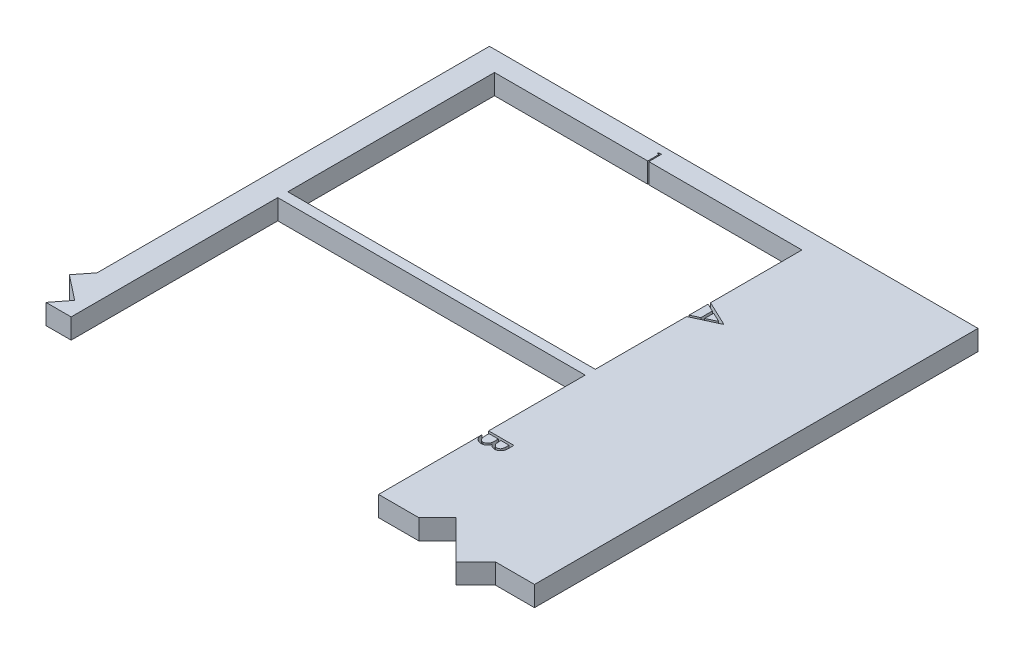
SolidWorks part; units mm, degrees
ref_plane "Front Plane" through (0, 0, 0) normal (0, 0, 1) x (1, 0, 0)
ref_plane "Top Plane" through (0, 0, 0) normal (0, 1, 0) x (1, 0, 0)
ref_plane "Right Plane" through (0, 0, 0) normal (1, 0, 0) x (0, 0, -1)
sketch "Sketch1" plane through (0, 0, 0) normal (0, 1, 0) x (1, 0, 0)
  line L0 (-146.05, 105.41) -> (-146.05, -110.49) construction
  line L1 (-146.05, -110.49) -> (-151.2076, -110.49)
  line L2 (-151.2076, -110.49) -> (-151.2076, 110.49)
  line L3 (-151.2076, 110.49) -> (151.0524, 110.49)
  line L4 (151.0524, -110.49) -> (151.0524, 110.49)
  line L5 (-55.88, 105.9659) -> (21.59, 105.9659) construction
  line L6 (-68.58, -110.49) -> (-55.88, -110.49)
  line L7 (21.59, -110.49) -> (34.29, -110.49)
  line L8 (-146.05, 105.9659) -> (-68.58, 105.9659) construction
  line L9 (-146.05, 105.41) -> (-68.58, 105.41)
  line L10 (-146.05, 105.41) -> (-146.05, 53.34)
  line L11 (-146.05, 53.34) -> (-68.58, 53.34)
  line L12 (-68.58, 105.41) -> (-68.58, 53.34)
  line L13 (-146.05, 50.8) -> (-68.58, 50.8)
  line L14 (-146.05, 50.8) -> (-146.05, -1.27)
  line L15 (-146.05, -1.27) -> (-68.58, -1.27)
  line L16 (-68.58, 50.8) -> (-68.58, -1.27)
  line L17 (-146.05, -3.81) -> (-68.58, -3.81)
  line L18 (-146.05, -3.81) -> (-146.05, -55.88)
  line L19 (-146.05, -55.88) -> (-68.58, -55.88)
  line L20 (-68.58, -3.81) -> (-68.58, -55.88)
  line L21 (-146.05, -58.42) -> (-68.58, -58.42)
  line L22 (-146.05, -58.42) -> (-146.05, -110.49)
  line L23 (34.29, 105.9659) -> (111.76, 105.9659) construction
  line L24 (-68.58, -58.42) -> (-68.58, -110.49)
  line L25 (-55.88, 105.41) -> (21.59, 105.41)
  line L26 (-55.88, 105.41) -> (-55.88, 53.34)
  line L27 (-55.88, 53.34) -> (21.59, 53.34)
  line L28 (21.59, 105.41) -> (21.59, 53.34)
  line L29 (34.29, 105.41) -> (111.76, 105.41)
  line L30 (34.29, 105.41) -> (34.29, 53.34)
  line L31 (34.29, 53.34) -> (111.76, 53.34)
  line L32 (111.76, 105.41) -> (111.76, 53.34)
  line L33 (-55.88, -1.27) -> (21.59, -1.27)
  line L34 (-55.88, -1.27) -> (-55.88, 50.8)
  line L35 (-55.88, 50.8) -> (21.59, 50.8)
  line L36 (21.59, -1.27) -> (21.59, 50.8)
  line L37 (-55.88, -55.88) -> (21.59, -55.88)
  line L38 (-55.88, -55.88) -> (-55.88, -3.81)
  line L39 (-55.88, -3.81) -> (21.59, -3.81)
  line L40 (21.59, -55.88) -> (21.59, -3.81)
  line L41 (132.8367, -58.42) -> (132.8367, -110.49) construction
  line L42 (-55.88, -110.49) -> (-55.88, -58.42)
  line L43 (-55.88, -58.42) -> (21.59, -58.42)
  line L44 (21.59, -110.49) -> (21.59, -58.42)
  line L45 (34.29, -1.27) -> (111.76, -1.27)
  line L46 (34.29, -1.27) -> (34.29, 50.8)
  line L47 (34.29, 50.8) -> (111.76, 50.8)
  line L48 (111.76, -1.27) -> (111.76, 50.8)
  line L49 (34.29, -55.88) -> (111.76, -55.88)
  line L50 (34.29, -55.88) -> (34.29, -3.81)
  line L51 (34.29, -3.81) -> (111.76, -3.81)
  line L52 (111.76, -55.88) -> (111.76, -3.81)
  line L54 (34.29, -110.49) -> (34.29, -58.42)
  line L55 (34.29, -58.42) -> (111.76, -58.42)
  line L56 (111.76, -110.49) -> (111.76, -58.42)
  line L57 (111.76, -110.49) -> (151.0524, -110.49)
  text T0 "D" font "Century Gothic" height in points 24
  text T1 "C" font "Century Gothic" height in points 24
  text T2 "B" font "Century Gothic" height in points 24
  text T3 "A" font "Century Gothic" height in points 24
  text T4 "3"
  text T5 "2"
  text T6 "1"
  point P0 (0, 0)
  dimension "D1" = 302.26
  dimension "D2" = 220.98
  dimension "D3" = 215.9
  dimension "D5" = 52.07
  dimension "D6" = 77.47
  dimension "D7" = 77.47
  dimension "D8" = 52.07
  dimension "D9" = 52.07
  dimension "D10" = 77.47
  dimension "D11" = 2.54
  dimension "D12" = 2.54
  dimension "D13" = 2.54
  dimension "D14" = 52.07
  dimension "D15" = 77.47
  dimension "D16" = 77.47
  dimension "D17" = 77.47
  dimension "D18" = 12.7
  dimension "D19" = 12.7
extrude "Boss-Extrude4" add sketch "Sketch1" along normal blind 5.08 contours L20 L17 L18 L19 | L16 L13 L14 L15 | L12 L9 L10 L11 | L28 L25 L26 L27 | L33 L36 L35 L34 | L37 L40 L39 L38 | L49 L52 L51 L50 | L45 L48 L47 L46 | L32 L29 L30 L31 | L3 L4 L57 L56 L55 L54 L7 L44 L43 L42 L6 L24 L21 L22 L1 L2
sketch "Sketch8" plane through (0, 5.08, 0) normal (0, 1, 0) x (1, 0, 0)
  text T0 "A" font "Century Gothic" height in points 24
  text T1 "B" font "Century Gothic" height in points 24
  text T2 "C" font "Century Gothic" height in points 24
  text T3 "D" font "Century Gothic" height in points 24
  text T4 "3"
  text T5 "2"
  text T6 "1"
extrude "Cut-Extrude9" cut sketch "Sketch8" against normal blind 5.08
sketch "Sketch9" plane through (0, 5.08, 0) normal (0, 1, 0) x (1, 0, 0)
  line L0 (34.29, -1.27) -> (27.9588, -1.27)
  line L1 (21.59, -110.49) -> (34.29, -110.49) construction
  line L2 (-151.2076, 110.49) -> (151.0524, 110.49) construction
  line L3 (27.9588, -1.27) -> (31.1244, 2.786)
  line L4 (31.1244, 2.786) -> (27.9515, 5.2854)
  line L5 (27.9515, 5.2854) -> (24.8644, 7.7173)
  line L6 (27.9445, 11.6273) -> (27.94, 15.7331)
  line L7 (27.94, 15.7331) -> (27.94, 110.49)
  line L8 (141.2048, -1.27) -> (151.0524, -1.27)
  line L9 (151.0524, -110.49) -> (151.0524, 110.49) construction
  line L10 (27.94, 110.49) -> (151.0524, 110.49)
  line L11 (24.8644, 7.7173) -> (27.9445, 11.6273)
  line L12 (151.0524, 110.49) -> (151.0524, -1.27)
  line L13 (151.0524, -110.49) -> (27.94, -110.49)
  line L14 (27.9588, -1.27) -> (24.8644, -4.8165)
  line L15 (27.9566, -13.9091) -> (27.94, -110.49)
  line L16 (24.8644, -4.8165) -> (27.9577, -7.5154)
  line L17 (27.9577, -7.5154) -> (31.1244, -10.2784)
  line L18 (31.1244, -10.2784) -> (27.9566, -13.9091)
  line L19 (151.0524, -110.49) -> (151.0524, -1.27)
  line L20 (121.9126, -1.27) -> (126.578, 3.3955)
  line L21 (126.578, 3.3955) -> (136.2242, -6.2507)
  line L22 (136.2242, -6.2507) -> (141.2048, -1.27)
  line L23 (121.9126, -1.27) -> (34.29, -1.27)
  line L24 (-151.2076, -110.49) -> (27.94, -110.49)
  line L25 (-151.2076, -110.49) -> (-151.2076, -1.27)
  line L26 (-151.2076, -110.49) -> (-151.2076, 110.49) construction
  line L27 (-151.2076, -1.27) -> (-66.3618, -1.27)
  line L28 (-66.3618, -1.27) -> (-62.9343, 2.1575)
  line L29 (-62.9343, 2.1575) -> (-59.5068, -1.27)
  line L30 (-59.5068, -1.27) -> (27.9588, -1.27)
  line L31 (-151.2076, -1.27) -> (-151.2076, 110.49)
  line L32 (-151.2076, 110.49) -> (27.94, 110.49)
extrude "Cut-Extrude20" cut sketch "Sketch9" against normal blind 5.08 contours L32 L31 L27 L28 L29 L30 L3 L4 L5 L11 L6 L7 | L30 L29 L28 L27 L25 L24 L15 L18 L17 L16 L14 | L20 L23 L0 L14 L16 L17 L18 L15 L13 L19 L8 L22 L21
